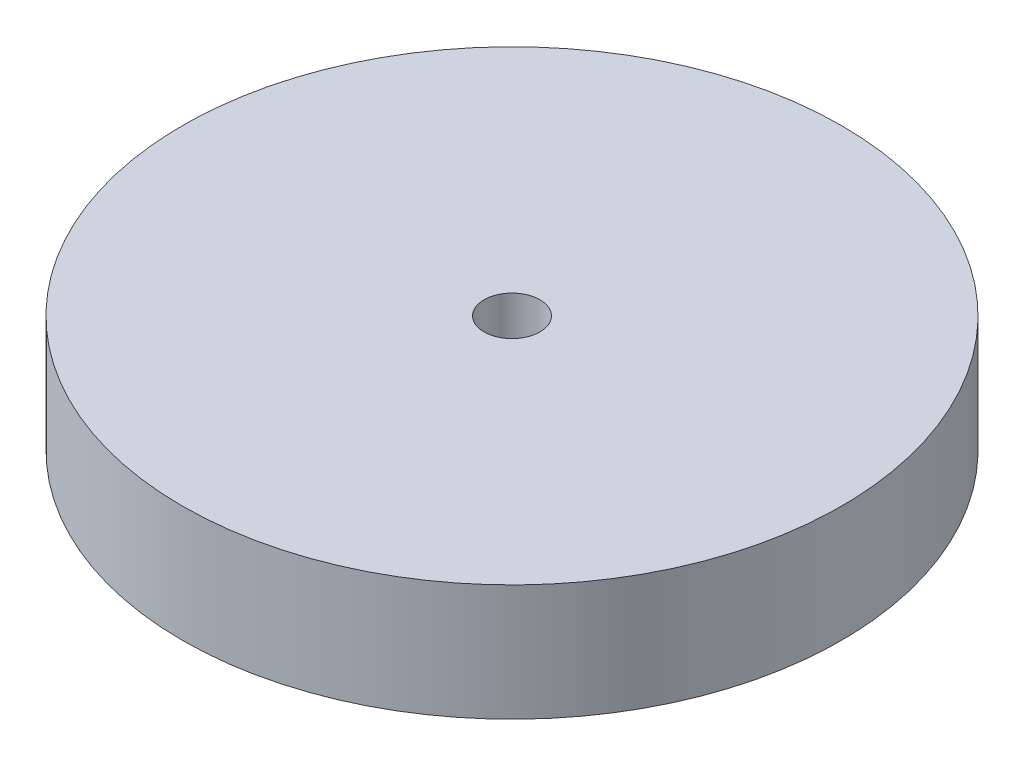
SolidWorks part; units mm, degrees
ref_plane "Front Plane" through (0, 0, 0) normal (0, 0, 1) x (1, 0, 0)
ref_plane "Top Plane" through (0, 0, 0) normal (0, 1, 0) x (1, 0, 0)
ref_plane "Right Plane" through (0, 0, 0) normal (1, 0, 0) x (0, 0, -1)
sketch "Sketch1" plane through (0, 0, 0) normal (0, 1, 0) x (1, 0, 0)
  circle A1 centre (0, 0) radius 85
extrude "Boss-Extrude1" add sketch "Sketch1" along normal blind 30
sketch "Sketch2" plane through (0, 30, 0) normal (0, 1, 0) x (1, 0, 0)
  circle A0 centre (0, 0) radius 7.2
extrude "Cut-Extrude1" cut sketch "Sketch2" against normal blind 120
